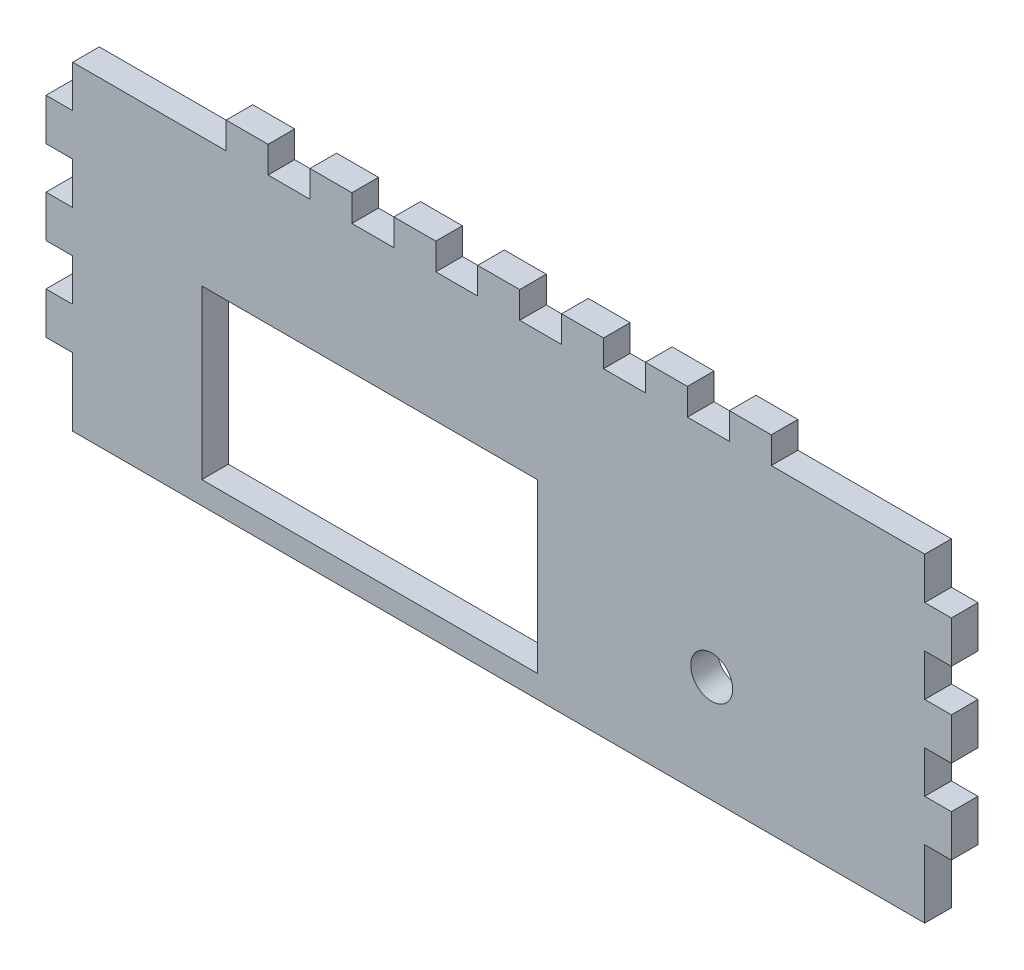
SolidWorks part; units mm, degrees
ref_plane "Front Plane" through (0, 0, 0) normal (0, 0, 1) x (1, 0, 0)
ref_plane "Top Plane" through (0, 0, 0) normal (0, 1, 0) x (1, 0, 0)
ref_plane "Right Plane" through (0, 0, 0) normal (1, 0, 0) x (0, 0, -1)
sketch "Sketch1" plane through (0, 0, 0) normal (0, 0, 1) x (1, 0, 0)
  line L0 (-101.6, -25.4) -> (0, -25.4) construction
  line L1 (-101.6, 0) -> (-83.3, 0)
  line L2 (0, 0) -> (0, -5)
  line L3 (0, -38.1) -> (-101.6, -38.1)
  line L4 (-101.6, 0) -> (-101.6, -5)
  line L6 (-86.2, -15.4) -> (-46.2, -15.4)
  line L7 (-28.3, 0) -> (-23.3, 0)
  line L8 (-23.3, 0) -> (-23.3, 3.175)
  line L9 (-23.3, 3.175) -> (-18.3, 3.175)
  line L10 (-86.2, -15.4) -> (-86.2, -35.4)
  line L11 (-86.2, -35.4) -> (-46.2, -35.4)
  line L12 (-46.2, -15.4) -> (-46.2, -35.4)
  line L16 (-83.3, 0) -> (-83.3, 3.175)
  line L17 (-83.3, 3.175) -> (-78.3, 3.175)
  line L18 (-78.3, 0) -> (-78.3, 3.175)
  line L19 (-78.3, 0) -> (-73.3, 0)
  line L20 (-73.3, 0) -> (-73.3, 3.175)
  line L21 (-73.3, 3.175) -> (-68.3, 3.175)
  line L22 (-68.3, 0) -> (-68.3, 3.175)
  line L23 (-68.3, 0) -> (-63.3, 0)
  line L24 (-63.3, 0) -> (-63.3, 3.175)
  line L25 (-63.3, 3.175) -> (-58.3, 3.175)
  line L26 (-58.3, 0) -> (-58.3, 3.175)
  line L27 (-58.3, 0) -> (-53.3, 0)
  line L28 (-53.3, 0) -> (-53.3, 3.175)
  line L29 (-53.3, 3.175) -> (-48.3, 3.175)
  line L30 (-48.3, 0) -> (-48.3, 3.175)
  line L31 (-48.3, 0) -> (-43.3, 0)
  line L32 (-43.3, 0) -> (-43.3, 3.175)
  line L33 (-43.3, 3.175) -> (-38.3, 3.175)
  line L34 (-38.3, 0) -> (-38.3, 3.175)
  line L35 (-38.3, 0) -> (-33.3, 0)
  line L36 (-33.3, 0) -> (-33.3, 3.175)
  line L37 (-33.3, 3.175) -> (-28.3, 3.175)
  line L38 (-28.3, 0) -> (-28.3, 3.175)
  line L39 (-18.3, 3.175) -> (-18.3, 0)
  line L40 (-18.3, 0) -> (0, 0)
  line L44 (-101.6, -10) -> (-101.6, -15)
  line L45 (-101.6, -5) -> (-104.775, -5)
  line L47 (-101.6, -15) -> (-104.775, -15)
  line L48 (-101.6, -10) -> (-104.775, -10)
  line L49 (-104.775, -5) -> (-104.775, -10)
  line L50 (-104.775, -15) -> (-104.775, -20)
  line L51 (-101.6, -20) -> (-104.775, -20)
  line L52 (-101.6, -20) -> (-101.6, -25)
  line L53 (-101.6, -25) -> (-104.775, -25)
  line L54 (-104.775, -25) -> (-104.775, -30)
  line L55 (-101.6, -30) -> (-104.775, -30)
  line L56 (-101.6, -30) -> (-101.6, -38.1)
  line L59 (-50.8, 27.452) -> (-50.8, -103.652) construction
  line L60 (3.175, -25) -> (3.175, -30)
  line L61 (3.175, -15) -> (3.175, -20)
  line L62 (3.175, -5) -> (3.175, -10)
  line L63 (3.175, -5) -> (0, -5)
  line L64 (3.175, -10) -> (0, -10)
  line L65 (3.175, -15) -> (0, -15)
  line L66 (3.175, -20) -> (0, -20)
  line L67 (3.175, -25) -> (0, -25)
  line L68 (3.175, -30) -> (0, -30)
  line L69 (0, -20) -> (0, -25)
  line L70 (0, -30) -> (0, -38.1)
  line L71 (0, -10) -> (0, -15)
  circle A1 centre (-25.4, -25.4) radius 2.5
  point P7 (-76.2, -25.4)
  point P72 (-50.8, -38.1)
  dimension "D3" = 10
  dimension "D5" = 12.7
  dimension "D6" = 3.175
  dimension "D1" = 5
  dimension "D2" = 10
  dimension "D4" = 25.4
  dimension "D7" = 38.1
  dimension "D9" = 5
  dimension "D10" = 5
  dimension "D12" = 101.6
  dimension "D13" = 30
  dimension "D8" = 3.175
  dimension "D14" = 25.4
  dimension "D17" = 5
  dimension "D18" = 5
  dimension "D11" = 3
extrude "Boss-Extrude1" add sketch "Sketch1" along normal blind 3.175
sketch "Sketch2" plane through (0, 0, 3.175) normal (0, 0, 1) x (1, 0, 0)
